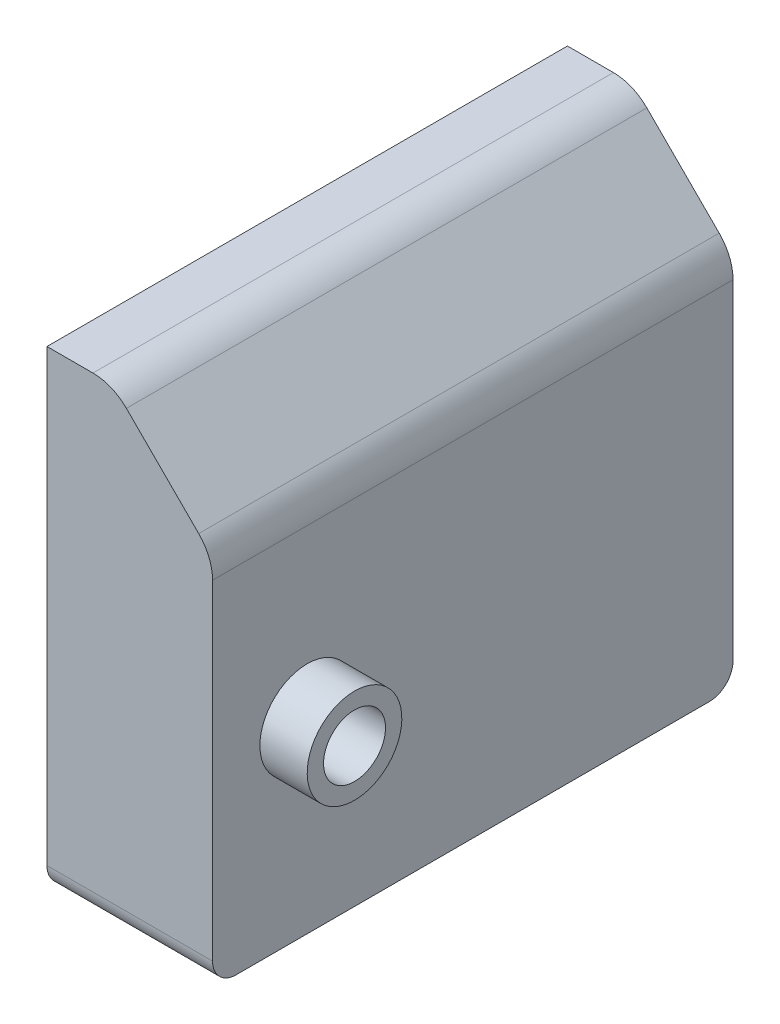
SolidWorks part; units mm, degrees
ref_plane "Front Plane" through (0, 0, 0) normal (0, 0, 1) x (1, 0, 0)
ref_plane "Top Plane" through (0, 0, 0) normal (0, 1, 0) x (1, 0, 0)
ref_plane "Right Plane" through (0, 0, 0) normal (1, 0, 0) x (0, 0, -1)
sketch "Sketch1" plane through (0, 0, 0) normal (0, 0, 1) x (1, 0, 0)
  line L0 (1, -21.7427) -> (14.8601, -21.7427)
  line L1 (14.8601, -21.7427) -> (36, -42.8826)
  line L2 (36, -42.8826) -> (36, -121.7427)
  line L3 (36, -121.7427) -> (1, -121.7427)
  line L4 (-27, -121.7427) -> (1, -121.7427) construction
  line L6 (1, -21.7427) -> (1, -121.7427)
  point P11 (0, 0)
  point P12 (0, 0)
extrude "Boss-Extrude1" add sketch "Sketch1" against normal blind 2
sketch "Sketch2" plane through (0, 0, -110) normal (0, 0, -1) x (-1, 0, 0)
  line L5 (-1, -121.7427) -> (-1, -21.7427)
  line L6 (-1, -21.7427) -> (-14.8601, -21.7427)
  line L7 (-14.8601, -21.7427) -> (-36, -42.8826)
  line L8 (-36, -42.8826) -> (-36, -121.7427)
  line L9 (-36, -121.7427) -> (-1, -121.7427)
  line L10 (-1, -121.7427) -> (-1, -21.7427)
  line L11 (-1, -21.7427) -> (-14.8601, -21.7427)
  line L12 (-14.8601, -21.7427) -> (-36, -42.8826)
  line L13 (-36, -42.8826) -> (-36, -121.7427)
  line L14 (-36, -121.7427) -> (-1, -121.7427)
  dimension "D1" = 0
extrude "Boss-Extrude2" add sketch "Sketch2" against normal blind 2 separate body
sketch "Sketch3" plane through (0, 0, -2) normal (0, 0, -1) x (-1, 0, 0)
  line L1 (-1, -23.7427) -> (-14.0317, -23.7427)
  line L2 (-14.0317, -23.7427) -> (-34, -43.711)
  line L3 (-34, -43.711) -> (-34, -119.7427)
  line L4 (-34, -119.7427) -> (-1, -119.7427)
  line L5 (-1, -121.7427) -> (-1, -21.7427)
  line L6 (-1, -21.7427) -> (-14.8601, -21.7427)
  line L7 (-14.8601, -21.7427) -> (-36, -42.8826)
  line L8 (-36, -42.8826) -> (-36, -121.7427)
  line L9 (-36, -121.7427) -> (-1, -121.7427)
  line L10 (-1, -121.7427) -> (-1, -119.7427)
  line L11 (-1, -21.7427) -> (-14.8601, -21.7427)
  line L12 (-14.8601, -21.7427) -> (-36, -42.8826)
  line L13 (-36, -42.8826) -> (-36, -121.7427)
  line L14 (-36, -121.7427) -> (-1, -121.7427)
  line L15 (-3, -119.7427) -> (-3, -23.7427) construction
  line L16 (-34, -119.7427) -> (-3, -119.7427) construction
  line L17 (-3, -23.7427) -> (-14.0317, -23.7427) construction
  line L18 (-1, -23.7427) -> (-1, -21.7427)
  line L19 (-1, -121.7427) -> (-1, -21.7427) construction
  dimension "D1" = 0
  dimension "D2" = 2
extrude "Boss-Extrude3" add sketch "Sketch3" along normal up to surface (106 mm away) up to face at (17.772, -65.9707, -108)
sketch "Sketch4" plane through (36, 0, 0) normal (1, 0, 0) x (0, 0, -1)
  line L0 (0, -82.3127) -> (20, -82.3127) construction
  line L1 (0, -121.7427) -> (0, -42.8826) construction
  circle A0 centre (20, -82.3127) radius 6.55
  circle A1 centre (20, -82.3127) radius 10
extrude "Boss-Extrude4" add sketch "Sketch4" along normal blind 10
fillet "Fillet1" radius 5 4 edges at (17.5, -119.7427, -2) (17.5, -119.7427, -108) (18.5, -121.7427, -110) (18.5, -121.7427, 0)
fillet "Fillet2" radius 10 4 edges at (36, -42.8826, -55) (34, -43.711, -55) (14.0317, -23.7427, -55) (14.8601, -21.7427, -55)
